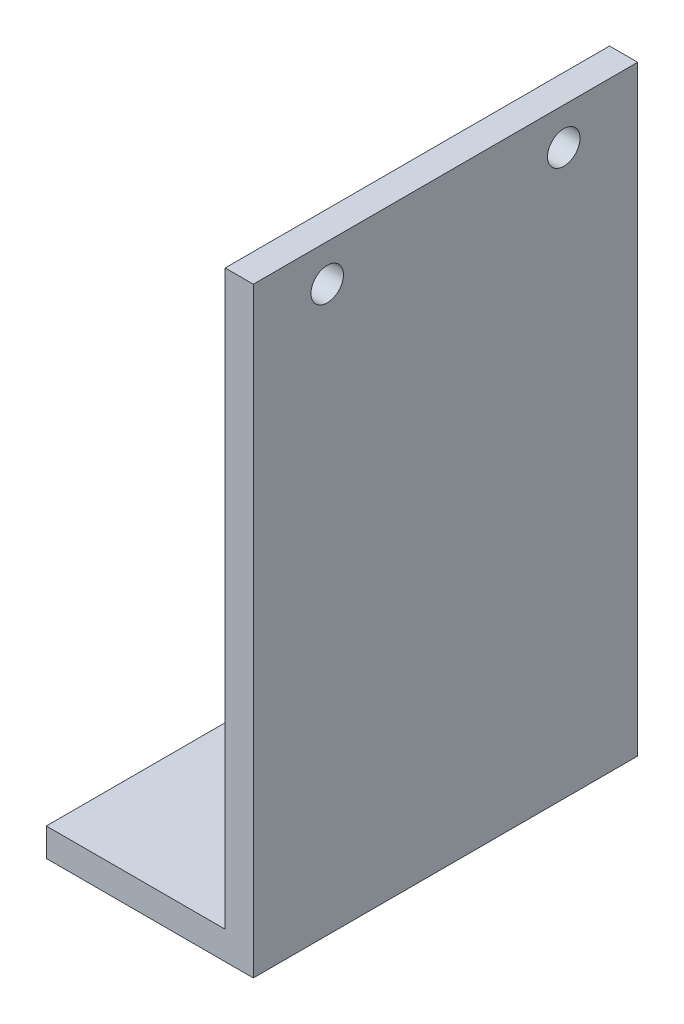
SolidWorks part; units mm, degrees
ref_plane "Front Plane" through (0, 0, 0) normal (0, 0, 1) x (1, 0, 0)
ref_plane "Top Plane" through (0, 0, 0) normal (0, 1, 0) x (1, 0, 0)
ref_plane "Right Plane" through (0, 0, 0) normal (1, 0, 0) x (0, 0, -1)
sketch "Sketch1" plane through (0, 0, 0) normal (0, 0, 1) x (1, 0, 0)
  line L0 (-77.4, 19.05) -> (-26.6, 19.05) construction
  line L1 (-77.4, 19.05) -> (-42.4, 19.05)
  line L2 (-42.4, 19.05) -> (-42.4, 120.65)
  line L3 (-77.4, 23.8125) -> (-47.1625, 23.8125)
  line L4 (-47.1625, 23.8125) -> (-47.1625, 120.65)
  line L5 (-47.1625, 120.65) -> (-42.4, 120.65)
  line L6 (-77.4, 19.05) -> (-77.4, 23.8125)
  point P9 (-47.1625, 120.65)
  dimension "D1" = 101.6
  dimension "D3" = 35
  dimension "D2" = 4.7625
extrude "Boss-Extrude1" add sketch "Sketch1" against normal blind 65
sketch "Sketch2" plane through (-47.1625, 0, 0) normal (-1, 0, 0) x (0, 0, 1)
  circle A0 centre (-12.5, 114.4177) radius 2.75 construction
  circle A1 centre (-12.5, 114.4177) radius 2.75
  circle A2 centre (-52.5, 114.4177) radius 2.75 construction
  circle A3 centre (-52.5, 114.4177) radius 2.75
extrude "Cut-Extrude1" cut sketch "Sketch2" against normal blind 10
